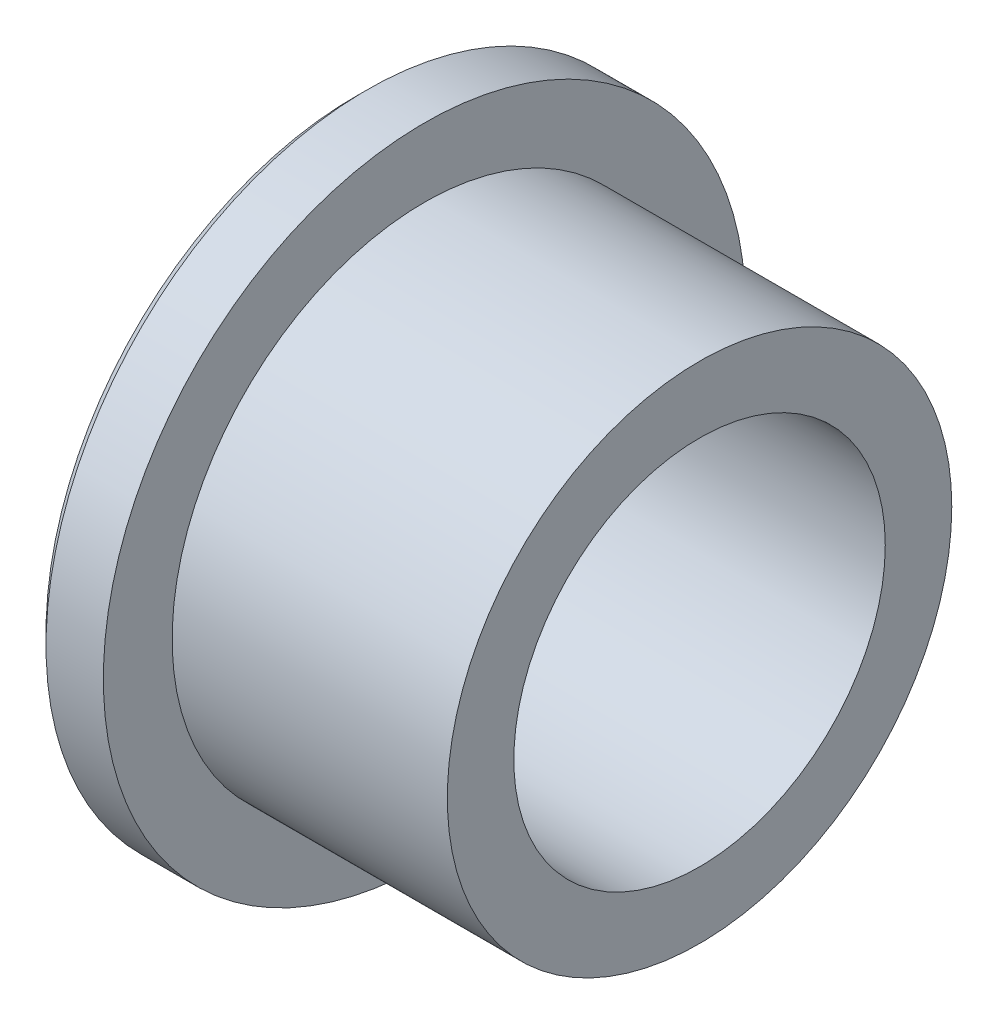
SolidWorks part; units mm, degrees
material "2.1016 (CuSn4)"
ref_plane "Płaszczyzna przednia" through (0, 0, 0) normal (0, 0, 1) x (1, 0, 0)
ref_plane "Płaszczyzna górna" through (0, 0, 0) normal (0, 1, 0) x (1, 0, 0)
ref_plane "Płaszczyzna prawa" through (0, 0, 0) normal (1, 0, 0) x (0, 0, -1)
sketch "Szkic1" plane through (0, 0, 0) normal (1, 0, 0) x (0, 0, -1)
  circle A0 centre (0, 0) radius 14
  circle A1 centre (0, 0) radius 8.1
  dimension "D1" = 28
  dimension "D2" = 16.2
extrude "Dodanie-wyciągnięcie1" add sketch "Szkic1" along normal blind 3
sketch "Szkic2" plane through (3, 0, 0) normal (1, 0, 0) x (0, 0, -1)
  circle A0 centre (0, 0) radius 8.1 construction
  circle A1 centre (0, 0) radius 8.1
  circle A2 centre (0, 0) radius 11
  dimension "D1" = 22
extrude "Dodanie-wyciągnięcie2" add sketch "Szkic2" along normal blind 12
chamfer "Sfazowanie1" distance 0.5 angle 45 1 edges at (0, 0, -14)
